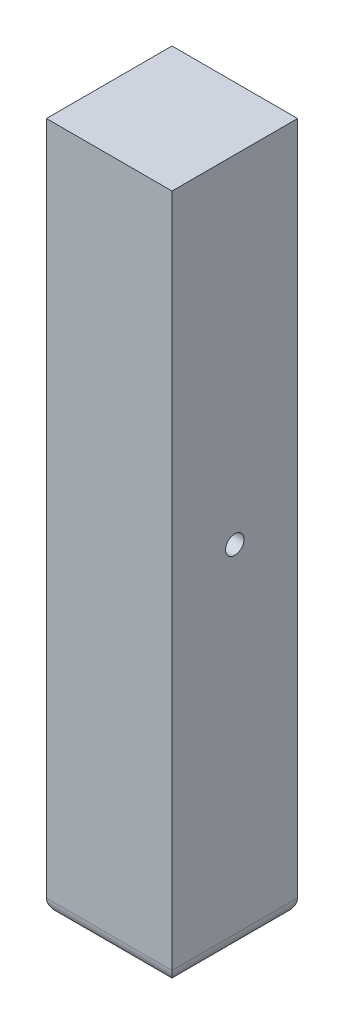
SolidWorks part; units mm, degrees
ref_plane "Front Plane" through (0, 0, 0) normal (0, 0, 1) x (1, 0, 0)
ref_plane "Top Plane" through (0, 0, 0) normal (0, 1, 0) x (1, 0, 0)
ref_plane "Right Plane" through (0, 0, 0) normal (1, 0, 0) x (0, 0, -1)
sketch "Sketch1" plane through (0, 0, 0) normal (0, 0, 1) x (1, 0, 0)
  line L1 (0, 0) -> (101.6, 0)
  line L2 (0, 0) -> (0, 558.8)
  line L3 (0, 558.8) -> (101.6, 558.8)
  line L4 (101.6, 0) -> (101.6, 558.8)
  dimension "D1" = 558.8
  dimension "D2" = 101.6
extrude "Boss-Extrude1" add sketch "Sketch1" along normal blind 101.6
fillet "Fillet2" radius 12.7 4 edges at (0, 0, 50.8) (50.8, 0, 0) (50.8, 0, 101.6) (101.6, 0, 50.8)
sketch "Sketch6" plane through (0, 0, 0) normal (-1, 0, 0) x (0, 0, 1)
  line L0 (101.6, 558.8) -> (101.6, 12.7) construction
  circle A0 centre (50.8, 285.75) radius 38.1
  dimension "D1" = 76.2
  dimension "D2" = 50.8
hole_wizard "CBORE for M12 Hex Head Bolt1" positions "Sketch7" profile "Sketch8" counterbore size "M12" standard "ANSI Metric" end condition up to next
sketch "Sketch7" plane through (0, 0, 0) normal (-1, 0, 0) x (0, 0, 1)
  point P0 (50.8, 285.75)
sketch "Sketch8" plane through (0, 285.75, 50.8) normal (0, 1, 0) x (0, 0, 1)
  line L0 (0, 0) -> (0, 101.6)
  line L1 (0, 101.6) -> (7.5, 101.6)
  line L3 (7.5, 101.6) -> (7.5, 7.95)
  line L4 (11.89, 7.95) -> (7.5, 7.95)
  line L5 (11.89, 7.95) -> (11.89, 0.025)
  line L6 (11.89, 0.025) -> (11.915, 0)
  line L7 (11.915, 0) -> (0, 0)
  line L8 (-11.89, 0.025) -> (-11.915, 0) construction
  line L11 (0, -6.35) -> (0, 107.95) construction
  dimension "Thru Hole Dia." = 15
  dimension "Thru Hole Depth" = 101.6
  dimension "C'Bore Dia." = 23.78
  dimension "C'Bore Depth" = 7.95
  dimension "Near C'Sink Dia." = 23.83
  dimension "Near C'Sink Angle" = 90
